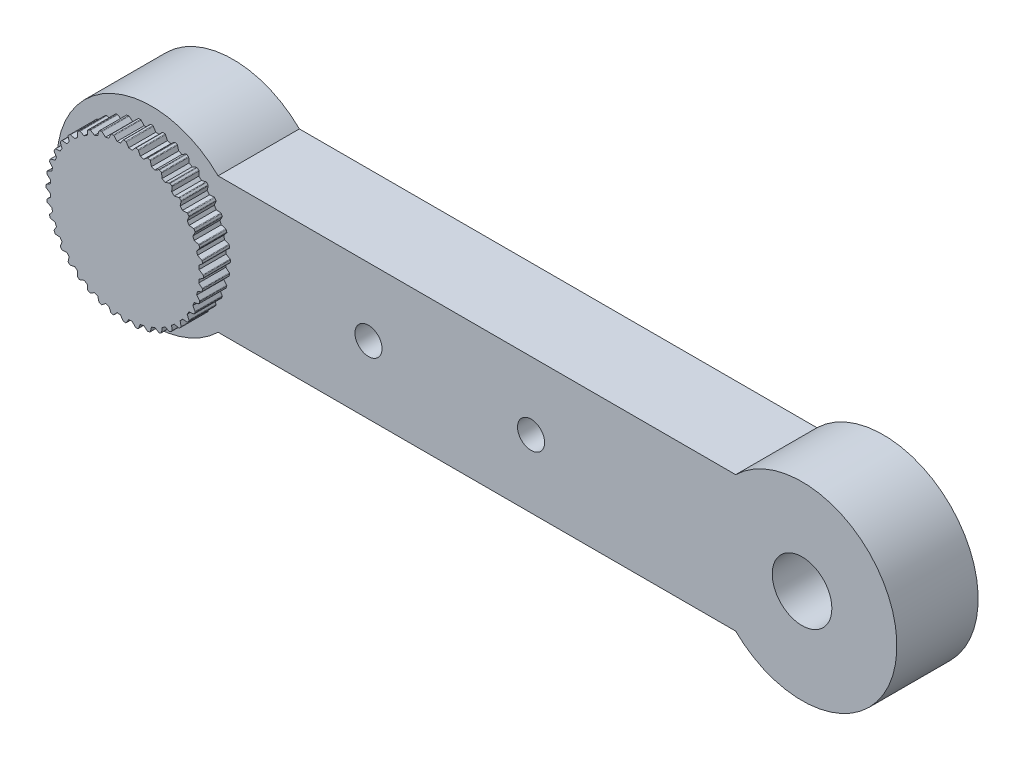
SolidWorks part; units mm, degrees
ref_plane "Front Plane" through (0, 0, 0) normal (0, 0, 1) x (1, 0, 0)
ref_plane "Top Plane" through (0, 0, 0) normal (0, 1, 0) x (1, 0, 0)
ref_plane "Right Plane" through (0, 0, 0) normal (1, 0, 0) x (0, 0, -1)
sketch "Sketch1" plane through (0, 0, 0) normal (0, 0, 1) x (1, 0, 0)
  line L1 (0.1755, 14.5089) -> (-0.1755, 14.5089)
  line L2 (2.5572, 14.2143) -> (2.8819, 13.465)
  line L3 (-0.3021, 14.4393) -> (-0.74, 13.75)
  line L4 (-0.74, 13.75) -> (-0.7536, 13.7285)
  line L5 (-0.7536, 13.7285) -> (-0.74, 13.75)
  line L6 (0.74, 13.75) -> (0.7536, 13.7285)
  line L7 (0.3021, 14.4393) -> (0.74, 13.75)
  line L8 (0.7536, 13.7285) -> (0.74, 13.75)
  line L9 (2.443, 14.3028) -> (2.0963, 14.3577)
  line L10 (1.9604, 14.3088) -> (1.4201, 13.6965)
  line L11 (1.4201, 13.6965) -> (1.4032, 13.6774)
  line L12 (2.8819, 13.465) -> (2.892, 13.4416)
  line L13 (4.7493, 13.6393) -> (4.9528, 12.8484)
  line L14 (4.6504, 13.7446) -> (4.3166, 13.853)
  line L15 (4.1747, 13.826) -> (3.5452, 13.3057)
  line L16 (3.5452, 13.3057) -> (3.5256, 13.2895)
  line L17 (4.9528, 12.8484) -> (4.9591, 12.8237)
  line L18 (6.8245, 12.7284) -> (6.9017, 11.9154)
  line L19 (6.7433, 12.8478) -> (6.4305, 13.0072)
  line L20 (6.2861, 13.0027) -> (5.583, 12.5873)
  line L21 (5.583, 12.5873) -> (5.5611, 12.5743)
  line L22 (6.9017, 11.9154) -> (6.9041, 11.8901)
  line L23 (8.7317, 11.5041) -> (8.6807, 10.689)
  line L24 (8.6701, 11.6348) -> (8.3861, 11.8411)
  line L25 (8.2428, 11.8593) -> (7.4834, 11.5589)
  line L26 (7.4834, 11.5589) -> (7.4597, 11.5496)
  line L27 (8.6807, 10.689) -> (8.6791, 10.6636)
  line L28 (10.4238, 9.9965) -> (10.246, 9.1995)
  line L29 (10.3835, 10.1352) -> (10.1352, 10.3835)
  line L30 (9.9965, 10.4238) -> (9.1995, 10.246)
  line L31 (9.1995, 10.246) -> (9.1746, 10.2404)
  line L32 (10.246, 9.1995) -> (10.2404, 9.1746)
  line L33 (11.8593, 8.2428) -> (11.5589, 7.4834)
  line L34 (11.8411, 8.3861) -> (11.6348, 8.6701)
  line L35 (11.5041, 8.7317) -> (10.689, 8.6807)
  line L36 (10.689, 8.6807) -> (10.6636, 8.6791)
  line L37 (11.5589, 7.4834) -> (11.5496, 7.4597)
  line L38 (13.0027, 6.2861) -> (12.5873, 5.583)
  line L39 (13.0072, 6.4305) -> (12.8478, 6.7433)
  line L40 (12.7284, 6.8245) -> (11.9154, 6.9017)
  line L41 (11.9154, 6.9017) -> (11.8901, 6.9041)
  line L42 (12.5873, 5.583) -> (12.5743, 5.5611)
  line L43 (13.826, 4.1747) -> (13.3057, 3.5452)
  line L44 (13.853, 4.3166) -> (13.7446, 4.6504)
  line L45 (13.6393, 4.7493) -> (12.8484, 4.9528)
  line L46 (12.8484, 4.9528) -> (12.8237, 4.9591)
  line L47 (13.3057, 3.5452) -> (13.2895, 3.5256)
  line L48 (14.3088, 1.9604) -> (13.6965, 1.4201)
  line L49 (14.3577, 2.0963) -> (14.3028, 2.443)
  line L50 (14.2143, 2.5572) -> (13.465, 2.8819)
  line L51 (13.465, 2.8819) -> (13.4416, 2.892)
  line L52 (13.6965, 1.4201) -> (13.6774, 1.4032)
  line L53 (14.4393, -0.3021) -> (13.75, -0.74)
  line L54 (14.5089, -0.1755) -> (14.5089, 0.1755)
  line L55 (14.4393, 0.3021) -> (13.75, 0.74)
  line L56 (13.75, 0.74) -> (13.7285, 0.7536)
  line L57 (13.75, -0.74) -> (13.7285, -0.7536)
  line L58 (14.2143, -2.5572) -> (13.465, -2.8819)
  line L59 (14.3028, -2.443) -> (14.3577, -2.0963)
  line L60 (14.3088, -1.9604) -> (13.6965, -1.4201)
  line L61 (13.6965, -1.4201) -> (13.6774, -1.4032)
  line L62 (13.465, -2.8819) -> (13.4416, -2.892)
  line L63 (13.6393, -4.7493) -> (12.8484, -4.9528)
  line L64 (13.7446, -4.6504) -> (13.853, -4.3166)
  line L65 (13.826, -4.1747) -> (13.3057, -3.5452)
  line L66 (13.3057, -3.5452) -> (13.2895, -3.5256)
  line L67 (12.8484, -4.9528) -> (12.8237, -4.9591)
  line L68 (12.7284, -6.8245) -> (11.9154, -6.9017)
  line L69 (12.8478, -6.7433) -> (13.0072, -6.4305)
  line L70 (13.0027, -6.2861) -> (12.5873, -5.583)
  line L71 (12.5873, -5.583) -> (12.5743, -5.5611)
  line L72 (11.9154, -6.9017) -> (11.8901, -6.9041)
  line L73 (11.5041, -8.7317) -> (10.689, -8.6807)
  line L74 (11.6348, -8.6701) -> (11.8411, -8.3861)
  line L75 (11.8593, -8.2428) -> (11.5589, -7.4834)
  line L76 (11.5589, -7.4834) -> (11.5496, -7.4597)
  line L77 (10.689, -8.6807) -> (10.6636, -8.6791)
  line L78 (9.9965, -10.4238) -> (9.1995, -10.246)
  line L79 (10.1352, -10.3835) -> (10.3835, -10.1352)
  line L80 (10.4238, -9.9965) -> (10.246, -9.1995)
  line L81 (10.246, -9.1995) -> (10.2404, -9.1746)
  line L82 (9.1995, -10.246) -> (9.1746, -10.2404)
  line L83 (8.2428, -11.8593) -> (7.4834, -11.5589)
  line L84 (8.3861, -11.8411) -> (8.6701, -11.6348)
  line L85 (8.7317, -11.5041) -> (8.6807, -10.689)
  line L86 (8.6807, -10.689) -> (8.6791, -10.6636)
  line L87 (7.4834, -11.5589) -> (7.4597, -11.5496)
  line L88 (6.2861, -13.0027) -> (5.583, -12.5873)
  line L89 (6.4305, -13.0072) -> (6.7433, -12.8478)
  line L90 (6.8245, -12.7284) -> (6.9017, -11.9154)
  line L91 (6.9017, -11.9154) -> (6.9041, -11.8901)
  line L92 (5.583, -12.5873) -> (5.5611, -12.5743)
  line L93 (4.1747, -13.826) -> (3.5452, -13.3057)
  line L94 (4.3166, -13.853) -> (4.6504, -13.7446)
  line L95 (4.7493, -13.6393) -> (4.9528, -12.8484)
  line L96 (4.9528, -12.8484) -> (4.9591, -12.8237)
  line L97 (3.5452, -13.3057) -> (3.5256, -13.2895)
  line L98 (1.9604, -14.3088) -> (1.4201, -13.6965)
  line L99 (2.0963, -14.3577) -> (2.443, -14.3028)
  line L100 (2.5572, -14.2143) -> (2.8819, -13.465)
  line L101 (2.8819, -13.465) -> (2.892, -13.4416)
  line L102 (1.4201, -13.6965) -> (1.4032, -13.6774)
  line L103 (-0.3021, -14.4393) -> (-0.74, -13.75)
  line L104 (-0.1755, -14.5089) -> (0.1755, -14.5089)
  line L105 (0.3021, -14.4393) -> (0.74, -13.75)
  line L106 (0.74, -13.75) -> (0.7536, -13.7285)
  line L107 (-0.74, -13.75) -> (-0.7536, -13.7285)
  line L108 (-2.5572, -14.2143) -> (-2.8819, -13.465)
  line L109 (-2.443, -14.3028) -> (-2.0963, -14.3577)
  line L110 (-1.9604, -14.3088) -> (-1.4201, -13.6965)
  line L111 (-1.4201, -13.6965) -> (-1.4032, -13.6774)
  line L112 (-2.8819, -13.465) -> (-2.892, -13.4416)
  line L113 (-4.7493, -13.6393) -> (-4.9528, -12.8484)
  line L114 (-4.6504, -13.7446) -> (-4.3166, -13.853)
  line L115 (-4.1747, -13.826) -> (-3.5452, -13.3057)
  line L116 (-3.5452, -13.3057) -> (-3.5256, -13.2895)
  line L117 (-4.9528, -12.8484) -> (-4.9591, -12.8237)
  line L118 (-6.8245, -12.7284) -> (-6.9017, -11.9154)
  line L119 (-6.7433, -12.8478) -> (-6.4305, -13.0072)
  line L120 (-6.2861, -13.0027) -> (-5.583, -12.5873)
  line L121 (-5.583, -12.5873) -> (-5.5611, -12.5743)
  line L122 (-6.9017, -11.9154) -> (-6.9041, -11.8901)
  line L123 (-8.7317, -11.5041) -> (-8.6807, -10.689)
  line L124 (-8.6701, -11.6348) -> (-8.3861, -11.8411)
  line L125 (-8.2428, -11.8593) -> (-7.4834, -11.5589)
  line L126 (-7.4834, -11.5589) -> (-7.4597, -11.5496)
  line L127 (-8.6807, -10.689) -> (-8.6791, -10.6636)
  line L128 (-10.4238, -9.9965) -> (-10.246, -9.1995)
  line L129 (-10.3835, -10.1352) -> (-10.1352, -10.3835)
  line L130 (-9.9965, -10.4238) -> (-9.1995, -10.246)
  line L131 (-9.1995, -10.246) -> (-9.1746, -10.2404)
  line L132 (-10.246, -9.1995) -> (-10.2404, -9.1746)
  line L133 (-11.8593, -8.2428) -> (-11.5589, -7.4834)
  line L134 (-11.8411, -8.3861) -> (-11.6348, -8.6701)
  line L135 (-11.5041, -8.7317) -> (-10.689, -8.6807)
  line L136 (-10.689, -8.6807) -> (-10.6636, -8.6791)
  line L137 (-11.5589, -7.4834) -> (-11.5496, -7.4597)
  line L138 (-13.0027, -6.2861) -> (-12.5873, -5.583)
  line L139 (-13.0072, -6.4305) -> (-12.8478, -6.7433)
  line L140 (-12.7284, -6.8245) -> (-11.9154, -6.9017)
  line L141 (-11.9154, -6.9017) -> (-11.8901, -6.9041)
  line L142 (-12.5873, -5.583) -> (-12.5743, -5.5611)
  line L143 (-13.826, -4.1747) -> (-13.3057, -3.5452)
  line L144 (-13.853, -4.3166) -> (-13.7446, -4.6504)
  line L145 (-13.6393, -4.7493) -> (-12.8484, -4.9528)
  line L146 (-12.8484, -4.9528) -> (-12.8237, -4.9591)
  line L147 (-13.3057, -3.5452) -> (-13.2895, -3.5256)
  line L148 (-14.3088, -1.9604) -> (-13.6965, -1.4201)
  line L149 (-14.3577, -2.0963) -> (-14.3028, -2.443)
  line L150 (-14.2143, -2.5572) -> (-13.465, -2.8819)
  line L151 (-13.465, -2.8819) -> (-13.4416, -2.892)
  line L152 (-13.6965, -1.4201) -> (-13.6774, -1.4032)
  line L153 (-14.4393, 0.3021) -> (-13.75, 0.74)
  line L154 (-14.5089, 0.1755) -> (-14.5089, -0.1755)
  line L155 (-14.4393, -0.3021) -> (-13.75, -0.74)
  line L156 (-13.75, -0.74) -> (-13.7285, -0.7536)
  line L157 (-13.75, 0.74) -> (-13.7285, 0.7536)
  line L158 (-14.2143, 2.5572) -> (-13.465, 2.8819)
  line L159 (-14.3028, 2.443) -> (-14.3577, 2.0963)
  line L160 (-14.3088, 1.9604) -> (-13.6965, 1.4201)
  line L161 (-13.6965, 1.4201) -> (-13.6774, 1.4032)
  line L162 (-13.465, 2.8819) -> (-13.4416, 2.892)
  line L163 (-13.6393, 4.7493) -> (-12.8484, 4.9528)
  line L164 (-13.7446, 4.6504) -> (-13.853, 4.3166)
  line L165 (-13.826, 4.1747) -> (-13.3057, 3.5452)
  line L166 (-13.3057, 3.5452) -> (-13.2895, 3.5256)
  line L167 (-12.8484, 4.9528) -> (-12.8237, 4.9591)
  line L168 (-12.7284, 6.8245) -> (-11.9154, 6.9017)
  line L169 (-12.8478, 6.7433) -> (-13.0072, 6.4305)
  line L170 (-13.0027, 6.2861) -> (-12.5873, 5.583)
  line L171 (-12.5873, 5.583) -> (-12.5743, 5.5611)
  line L172 (-11.9154, 6.9017) -> (-11.8901, 6.9041)
  line L173 (-11.5041, 8.7317) -> (-10.689, 8.6807)
  line L174 (-11.6348, 8.6701) -> (-11.8411, 8.3861)
  line L175 (-11.8593, 8.2428) -> (-11.5589, 7.4834)
  line L176 (-11.5589, 7.4834) -> (-11.5496, 7.4597)
  line L177 (-10.689, 8.6807) -> (-10.6636, 8.6791)
  line L178 (-9.9965, 10.4238) -> (-9.1995, 10.246)
  line L179 (-10.1352, 10.3835) -> (-10.3835, 10.1352)
  line L180 (-10.4238, 9.9965) -> (-10.246, 9.1995)
  line L181 (-10.246, 9.1995) -> (-10.2404, 9.1746)
  line L182 (-9.1995, 10.246) -> (-9.1746, 10.2404)
  line L183 (-8.2428, 11.8593) -> (-7.4834, 11.5589)
  line L184 (-8.3861, 11.8411) -> (-8.6701, 11.6348)
  line L185 (-8.7317, 11.5041) -> (-8.6807, 10.689)
  line L186 (-8.6807, 10.689) -> (-8.6791, 10.6636)
  line L187 (-7.4834, 11.5589) -> (-7.4597, 11.5496)
  line L188 (-6.2861, 13.0027) -> (-5.583, 12.5873)
  line L189 (-6.4305, 13.0072) -> (-6.7433, 12.8478)
  line L190 (-6.8245, 12.7284) -> (-6.9017, 11.9154)
  line L191 (-6.9017, 11.9154) -> (-6.9041, 11.8901)
  line L192 (-5.583, 12.5873) -> (-5.5611, 12.5743)
  line L193 (-4.1747, 13.826) -> (-3.5452, 13.3057)
  line L194 (-4.3166, 13.853) -> (-4.6504, 13.7446)
  line L195 (-4.7493, 13.6393) -> (-4.9528, 12.8484)
  line L196 (-4.9528, 12.8484) -> (-4.9591, 12.8237)
  line L197 (-3.5452, 13.3057) -> (-3.5256, 13.2895)
  line L198 (-1.9604, 14.3088) -> (-1.4201, 13.6965)
  line L199 (-2.0963, 14.3577) -> (-2.443, 14.3028)
  line L200 (-2.5572, 14.2143) -> (-2.8819, 13.465)
  line L201 (-2.8819, 13.465) -> (-2.892, 13.4416)
  line L202 (-1.4201, 13.6965) -> (-1.4032, 13.6774)
  arc A0 (-0.7531, 13.7294) -> (-1.4039, 13.6781) centre (0, 0) ccw
  arc A2 (0.3021, 14.4393) -> (0.1755, 14.5089) centre (0.1755, 14.3589) ccw
  arc A3 (-0.1755, 14.5089) -> (-0.3021, 14.4393) centre (-0.1755, 14.3589) ccw
  arc A4 (2.5572, 14.2143) -> (2.443, 14.3028) centre (2.4196, 14.1547) ccw
  arc A5 (2.0963, 14.3577) -> (1.9604, 14.3088) centre (2.0729, 14.2096) ccw
  arc A6 (4.7493, 13.6393) -> (4.6504, 13.7446) centre (4.6041, 13.6019) ccw
  arc A7 (4.3166, 13.853) -> (4.1747, 13.826) centre (4.2702, 13.7104) ccw
  arc A8 (6.8245, 12.7284) -> (6.7433, 12.8478) centre (6.6752, 12.7142) ccw
  arc A9 (6.4305, 13.0072) -> (6.2861, 13.0027) centre (6.3624, 12.8736) ccw
  arc A10 (8.7317, 11.5041) -> (8.6701, 11.6348) centre (8.5819, 11.5134) ccw
  arc A11 (8.3861, 11.8411) -> (8.2428, 11.8593) centre (8.298, 11.7198) ccw
  arc A12 (10.4238, 9.9965) -> (10.3835, 10.1352) centre (10.2774, 10.0292) ccw
  arc A13 (10.1352, 10.3835) -> (9.9965, 10.4238) centre (10.0292, 10.2774) ccw
  arc A14 (11.8593, 8.2428) -> (11.8411, 8.3861) centre (11.7198, 8.298) ccw
  arc A15 (11.6348, 8.6701) -> (11.5041, 8.7317) centre (11.5134, 8.5819) ccw
  arc A16 (13.0027, 6.2861) -> (13.0072, 6.4305) centre (12.8736, 6.3624) ccw
  arc A17 (12.8478, 6.7433) -> (12.7284, 6.8245) centre (12.7142, 6.6752) ccw
  arc A18 (13.826, 4.1747) -> (13.853, 4.3166) centre (13.7104, 4.2702) ccw
  arc A19 (13.7446, 4.6504) -> (13.6393, 4.7493) centre (13.6019, 4.6041) ccw
  arc A20 (14.3088, 1.9604) -> (14.3577, 2.0963) centre (14.2096, 2.0729) ccw
  arc A21 (14.3028, 2.443) -> (14.2143, 2.5572) centre (14.1547, 2.4196) ccw
  arc A22 (14.4393, -0.3021) -> (14.5089, -0.1755) centre (14.3589, -0.1755) ccw
  arc A23 (14.5089, 0.1755) -> (14.4393, 0.3021) centre (14.3589, 0.1755) ccw
  arc A24 (14.2143, -2.5572) -> (14.3028, -2.443) centre (14.1547, -2.4196) ccw
  arc A25 (14.3577, -2.0963) -> (14.3088, -1.9604) centre (14.2096, -2.0729) ccw
  arc A26 (13.6393, -4.7493) -> (13.7446, -4.6504) centre (13.6019, -4.6041) ccw
  arc A27 (13.853, -4.3166) -> (13.826, -4.1747) centre (13.7104, -4.2702) ccw
  arc A28 (12.7284, -6.8245) -> (12.8478, -6.7433) centre (12.7142, -6.6752) ccw
  arc A29 (13.0072, -6.4305) -> (13.0027, -6.2861) centre (12.8736, -6.3624) ccw
  arc A30 (11.5041, -8.7317) -> (11.6348, -8.6701) centre (11.5134, -8.5819) ccw
  arc A31 (11.8411, -8.3861) -> (11.8593, -8.2428) centre (11.7198, -8.298) ccw
  arc A32 (9.9965, -10.4238) -> (10.1352, -10.3835) centre (10.0292, -10.2774) ccw
  arc A33 (10.3835, -10.1352) -> (10.4238, -9.9965) centre (10.2774, -10.0292) ccw
  arc A34 (8.2428, -11.8593) -> (8.3861, -11.8411) centre (8.298, -11.7198) ccw
  arc A35 (8.6701, -11.6348) -> (8.7317, -11.5041) centre (8.5819, -11.5134) ccw
  arc A36 (6.2861, -13.0027) -> (6.4305, -13.0072) centre (6.3624, -12.8736) ccw
  arc A37 (6.7433, -12.8478) -> (6.8245, -12.7284) centre (6.6752, -12.7142) ccw
  arc A38 (4.1747, -13.826) -> (4.3166, -13.853) centre (4.2702, -13.7104) ccw
  arc A39 (4.6504, -13.7446) -> (4.7493, -13.6393) centre (4.6041, -13.6019) ccw
  arc A40 (1.9604, -14.3088) -> (2.0963, -14.3577) centre (2.0729, -14.2096) ccw
  arc A41 (2.443, -14.3028) -> (2.5572, -14.2143) centre (2.4196, -14.1547) ccw
  arc A42 (-0.3021, -14.4393) -> (-0.1755, -14.5089) centre (-0.1755, -14.3589) ccw
  arc A43 (0.1755, -14.5089) -> (0.3021, -14.4393) centre (0.1755, -14.3589) ccw
  arc A44 (-2.5572, -14.2143) -> (-2.443, -14.3028) centre (-2.4196, -14.1547) ccw
  arc A45 (-2.0963, -14.3577) -> (-1.9604, -14.3088) centre (-2.0729, -14.2096) ccw
  arc A46 (-4.7493, -13.6393) -> (-4.6504, -13.7446) centre (-4.6041, -13.6019) ccw
  arc A47 (-4.3166, -13.853) -> (-4.1747, -13.826) centre (-4.2702, -13.7104) ccw
  arc A48 (-6.8245, -12.7284) -> (-6.7433, -12.8478) centre (-6.6752, -12.7142) ccw
  arc A49 (-6.4305, -13.0072) -> (-6.2861, -13.0027) centre (-6.3624, -12.8736) ccw
  arc A50 (-8.7317, -11.5041) -> (-8.6701, -11.6348) centre (-8.5819, -11.5134) ccw
  arc A51 (-8.3861, -11.8411) -> (-8.2428, -11.8593) centre (-8.298, -11.7198) ccw
  arc A52 (-10.4238, -9.9965) -> (-10.3835, -10.1352) centre (-10.2774, -10.0292) ccw
  arc A53 (-10.1352, -10.3835) -> (-9.9965, -10.4238) centre (-10.0292, -10.2774) ccw
  arc A54 (-11.8593, -8.2428) -> (-11.8411, -8.3861) centre (-11.7198, -8.298) ccw
  arc A55 (-11.6348, -8.6701) -> (-11.5041, -8.7317) centre (-11.5134, -8.5819) ccw
  arc A56 (-13.0027, -6.2861) -> (-13.0072, -6.4305) centre (-12.8736, -6.3624) ccw
  arc A57 (-12.8478, -6.7433) -> (-12.7284, -6.8245) centre (-12.7142, -6.6752) ccw
  arc A58 (-13.826, -4.1747) -> (-13.853, -4.3166) centre (-13.7104, -4.2702) ccw
  arc A59 (-13.7446, -4.6504) -> (-13.6393, -4.7493) centre (-13.6019, -4.6041) ccw
  arc A60 (-14.3088, -1.9604) -> (-14.3577, -2.0963) centre (-14.2096, -2.0729) ccw
  arc A61 (-14.3028, -2.443) -> (-14.2143, -2.5572) centre (-14.1547, -2.4196) ccw
  arc A62 (-14.4393, 0.3021) -> (-14.5089, 0.1755) centre (-14.3589, 0.1755) ccw
  arc A63 (-14.5089, -0.1755) -> (-14.4393, -0.3021) centre (-14.3589, -0.1755) ccw
  arc A64 (-14.2143, 2.5572) -> (-14.3028, 2.443) centre (-14.1547, 2.4196) ccw
  arc A65 (-14.3577, 2.0963) -> (-14.3088, 1.9604) centre (-14.2096, 2.0729) ccw
  arc A66 (-13.6393, 4.7493) -> (-13.7446, 4.6504) centre (-13.6019, 4.6041) ccw
  arc A67 (-13.853, 4.3166) -> (-13.826, 4.1747) centre (-13.7104, 4.2702) ccw
  arc A68 (-12.7284, 6.8245) -> (-12.8478, 6.7433) centre (-12.7142, 6.6752) ccw
  arc A69 (-13.0072, 6.4305) -> (-13.0027, 6.2861) centre (-12.8736, 6.3624) ccw
  arc A70 (-11.5041, 8.7317) -> (-11.6348, 8.6701) centre (-11.5134, 8.5819) ccw
  arc A71 (-11.8411, 8.3861) -> (-11.8593, 8.2428) centre (-11.7198, 8.298) ccw
  arc A72 (-9.9965, 10.4238) -> (-10.1352, 10.3835) centre (-10.0292, 10.2774) ccw
  arc A73 (-10.3835, 10.1352) -> (-10.4238, 9.9965) centre (-10.2774, 10.0292) ccw
  arc A74 (-8.2428, 11.8593) -> (-8.3861, 11.8411) centre (-8.298, 11.7198) ccw
  arc A75 (-8.6701, 11.6348) -> (-8.7317, 11.5041) centre (-8.5819, 11.5134) ccw
  arc A76 (-6.2861, 13.0027) -> (-6.4305, 13.0072) centre (-6.3624, 12.8736) ccw
  arc A77 (-6.7433, 12.8478) -> (-6.8245, 12.7284) centre (-6.6752, 12.7142) ccw
  arc A78 (-4.1747, 13.826) -> (-4.3166, 13.853) centre (-4.2702, 13.7104) ccw
  arc A79 (-4.6504, 13.7446) -> (-4.7493, 13.6393) centre (-4.6041, 13.6019) ccw
  arc A80 (-1.9604, 14.3088) -> (-2.0963, 14.3577) centre (-2.0729, 14.2096) ccw
  arc A81 (-2.443, 14.3028) -> (-2.5572, 14.2143) centre (-2.4196, 14.1547) ccw
  arc A82 (-2.8916, 13.4425) -> (-3.5264, 13.2901) centre (0, 0) ccw
  arc A83 (1.4039, 13.6781) -> (0.7531, 13.7294) centre (0, 0) ccw
  arc A84 (-6.904, 11.891) -> (-7.4606, 11.55) centre (0, 0) ccw
  arc A85 (-8.6792, 10.6646) -> (-9.1756, 10.2407) centre (0, 0) ccw
  arc A86 (-10.2407, 9.1756) -> (-10.6646, 8.6792) centre (0, 0) ccw
  arc A87 (-11.55, 7.4606) -> (-11.891, 6.904) centre (0, 0) ccw
  arc A88 (-12.5749, 5.562) -> (-12.8247, 4.9589) centre (0, 0) ccw
  arc A89 (-13.2901, 3.5264) -> (-13.4425, 2.8916) centre (0, 0) ccw
  arc A90 (-13.6781, 1.4039) -> (-13.7294, 0.7531) centre (0, 0) ccw
  arc A91 (-13.7294, -0.7531) -> (-13.6781, -1.4039) centre (0, 0) ccw
  arc A92 (-13.4425, -2.8916) -> (-13.2901, -3.5264) centre (0, 0) ccw
  arc A93 (-11.891, -6.904) -> (-11.55, -7.4606) centre (0, 0) ccw
  arc A94 (-12.8247, -4.9589) -> (-12.5749, -5.562) centre (0, 0) ccw
  arc A95 (-10.6646, -8.6792) -> (-10.2407, -9.1756) centre (0, 0) ccw
  arc A96 (-9.1756, -10.2407) -> (-8.6792, -10.6646) centre (0, 0) ccw
  arc A97 (-7.4606, -11.55) -> (-6.904, -11.891) centre (0, 0) ccw
  arc A98 (-5.562, -12.5749) -> (-4.9589, -12.8247) centre (0, 0) ccw
  arc A99 (-3.5264, -13.2901) -> (-2.8916, -13.4425) centre (0, 0) ccw
  arc A100 (-1.4039, -13.6781) -> (-0.7531, -13.7294) centre (0, 0) ccw
  arc A101 (0.7531, -13.7294) -> (1.4039, -13.6781) centre (0, 0) ccw
  arc A102 (2.8916, -13.4425) -> (3.5264, -13.2901) centre (0, 0) ccw
  arc A103 (4.9589, -12.8247) -> (5.562, -12.5749) centre (0, 0) ccw
  arc A104 (6.904, -11.891) -> (7.4606, -11.55) centre (0, 0) ccw
  arc A105 (8.6792, -10.6646) -> (9.1756, -10.2407) centre (0, 0) ccw
  arc A106 (11.55, -7.4606) -> (11.891, -6.904) centre (0, 0) ccw
  arc A107 (10.2407, -9.1756) -> (10.6646, -8.6792) centre (0, 0) ccw
  arc A108 (12.5749, -5.562) -> (12.8247, -4.9589) centre (0, 0) ccw
  arc A109 (13.2901, -3.5264) -> (13.4425, -2.8916) centre (0, 0) ccw
  arc A110 (13.6781, -1.4039) -> (13.7294, -0.7531) centre (0, 0) ccw
  arc A111 (13.7294, 0.7531) -> (13.6781, 1.4039) centre (0, 0) ccw
  arc A112 (12.8247, 4.9589) -> (12.5749, 5.562) centre (0, 0) ccw
  arc A113 (11.891, 6.904) -> (11.55, 7.4606) centre (0, 0) ccw
  arc A114 (10.6646, 8.6792) -> (10.2407, 9.1756) centre (0, 0) ccw
  arc A115 (9.1756, 10.2407) -> (8.6792, 10.6646) centre (0, 0) ccw
  arc A116 (7.4606, 11.55) -> (6.904, 11.891) centre (0, 0) ccw
  arc A117 (5.562, 12.5749) -> (4.9589, 12.8247) centre (0, 0) ccw
  arc A118 (3.5264, 13.2901) -> (2.8916, 13.4425) centre (0, 0) ccw
  arc A119 (-4.9589, 12.8247) -> (-5.562, 12.5749) centre (0, 0) ccw
  arc A120 (13.4425, 2.8916) -> (13.2901, 3.5264) centre (0, 0) ccw
  point P11 (0, 14.5089)
  point P16 (0.2579, 14.5089)
  point P19 (-0.2579, 14.5089)
  point P410 (0, 0)
  dimension "D1" = 27.5
  dimension "D2" = 40
  dimension "D4" = 0.15
extrude "Boss-Extrude2" add sketch "Sketch1" along normal blind 5
sketch "Sketch2" plane through (0, 0, 0) normal (0, 0, -1) x (-1, 0, 0)
  line L1 (0, -12.5) -> (-120, -12.5)
  line L2 (0, -12.5) -> (0, 12.5)
  line L3 (0, 12.5) -> (-120, 12.5)
  line L4 (-120, -12.5) -> (-120, 12.5)
  circle A0 centre (0, 0) radius 17.5
  circle A1 centre (-120, 0) radius 17.5
  dimension "D1" = 12.5
ref_plane "Plane1" through (-4.6504, -13.7446, 5) normal (0, 0, -1) x (-1, 0, 0)
sketch "Sketch3" plane through (-4.6504, -13.7446, 5) normal (0, 0, -1) x (-1, 0, 0)
extrude "Boss-Extrude3" add sketch "Sketch2" along normal blind 15 contours L3 A1 L1 L4 | L1 A1 L3 L4 | A1 L1 A0 L3 | L3 A0 L1 L2 | L1 A0 L3 L2
sketch "Sketch4" plane through (0, 0, 0) normal (0, 0, 1) x (1, 0, 0)
  circle A0 centre (40, 0) radius 2.5
  circle A1 centre (70, 0) radius 2.5
  dimension "D3" = 5
  dimension "D4" = 5
  dimension "D1" = 40
  dimension "D2" = 30
extrude "Cut-Extrude1" cut sketch "Sketch4" against normal blind 15
sketch "Sketch5" plane through (0, 0, 0) normal (0, 0, 1) x (1, 0, 0)
  circle A0 centre (120, 0) radius 5.5
extrude "Cut-Extrude2" cut sketch "Sketch5" against normal blind 15
